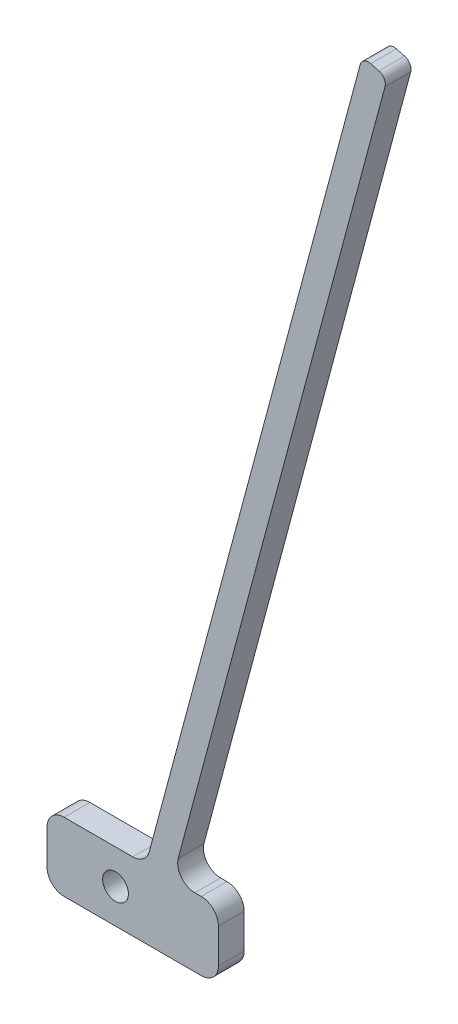
SolidWorks part; units mm, degrees
ref_plane "Front Plane" through (0, 0, 0) normal (0, 0, 1) x (1, 0, 0)
ref_plane "Top Plane" through (0, 0, 0) normal (0, 1, 0) x (1, 0, 0)
ref_plane "Right Plane" through (0, 0, 0) normal (1, 0, 0) x (0, 0, -1)
sketch "Sketch1" plane through (0, 0, 0) normal (0, 0, 1) x (1, 0, 0)
  line L6 (-11.5347, -2) -> (-11.5347, -6)
  line L7 (-9.5347, -8) -> (6.4653, -8)
  line L8 (8.4653, -6) -> (8.4653, -2)
  line L9 (6.4653, 0) -> (5.7123, 0)
  line L10 (3.7804, 2.5176) -> (27.8959, 92.5176)
  line L11 (27.1887, 93.7424) -> (26.2228, 94.0012)
  line L12 (24.9981, 93.2941) -> (0.3972, 1.4824)
  line L13 (-1.5347, 0) -> (-9.5347, 0)
  circle A3 centre (-3.5347, -4) radius 1.5
  arc A4 (0.3972, 1.4824) -> (-1.5347, 0) centre (-1.5347, 2) cw
  arc A5 (6.4653, 0) -> (8.4653, -2) centre (6.4653, -2) cw
  arc A6 (8.4653, -6) -> (6.4653, -8) centre (6.4653, -6) cw
  arc A7 (-9.5347, -8) -> (-11.5347, -6) centre (-9.5347, -6) cw
  arc A8 (-11.5347, -2) -> (-9.5347, 0) centre (-9.5347, -2) cw
  arc A9 (3.7804, 2.5176) -> (5.7123, 0) centre (5.7123, 2) ccw
  arc A10 (27.8959, 92.5176) -> (27.1887, 93.7424) centre (26.9299, 92.7765) ccw
  arc A11 (26.2228, 94.0012) -> (24.9981, 93.2941) centre (25.964, 93.0353) ccw
  point P13 (0, 0)
  point P18 (8.4653, -8)
  point P23 (-11.5347, -8)
  point P26 (-11.5347, 0)
  point P31 (28.1547, 93.4836)
  point P34 (25.2569, 94.26)
  dimension "D1" = 3
  dimension "D2" = 20
  dimension "D9" = 4
  dimension "D4" = 2
  dimension "D6" = 2
  dimension "D7" = 1
  dimension "D10" = 3
  dimension "D3" = 8
  dimension "D5" = 10
  dimension "D8" = 105
  dimension "D11" = 8
  dimension "D12" = 90
extrude "Boss-Extrude1" add sketch "Sketch1" along normal blind 3
